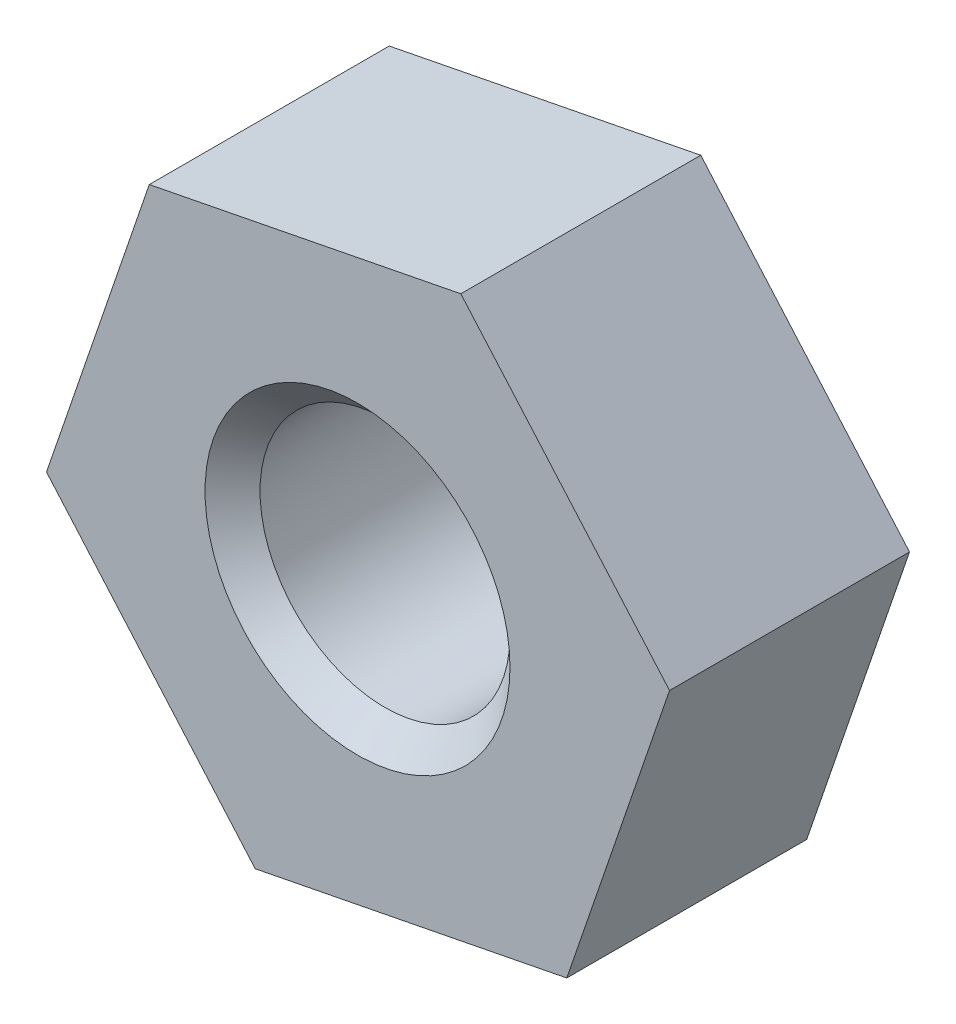
SolidWorks part; units mm, degrees
ref_plane "Front Plane" through (0, 0, 0) normal (0, 0, 1) x (1, 0, 0)
ref_plane "Top Plane" through (0, 0, 0) normal (0, 1, 0) x (1, 0, 0)
ref_plane "Right Plane" through (0, 0, 0) normal (1, 0, 0) x (0, 0, -1)
sketch "Sketch1" plane through (0, 0, 0) normal (0, 0, 1) x (1, 0, 0)
  line L1 (2.0878, -2.3926) -> (3.1159, 0.6118)
  line L2 (3.1159, 0.6118) -> (1.0281, 3.0044)
  line L3 (1.0281, 3.0044) -> (-2.0878, 2.3926)
  line L4 (-2.0878, 2.3926) -> (-3.1159, -0.6118)
  line L5 (-3.1159, -0.6118) -> (-1.0281, -3.0044)
  line L6 (-1.0281, -3.0044) -> (2.0878, -2.3926)
  circle A0 centre (0, 0) radius 2.75 construction
  dimension "D1" = 5.5
extrude "Boss-Extrude1" add sketch "Sketch1" along normal blind 2.4
hole_wizard "M3 Tapped Hole3" positions "3DSketch5" profile "Sketch5" tap size "M3" standard "ISO" end condition through all
sketch3d "3DSketch5"
  point P0 (-0.005, 0.0161, 2.4)
sketch "Sketch5" plane through (-0.005, 0.0161, 2.4) normal (1, 0, 0) x (0, -1, 0)
  line L0 (0, 0) -> (0, 2.4)
  line L1 (0, 2.4) -> (1.25, 2.4)
  line L2 (1.25, 2.4) -> (1.25, 0.275)
  line L3 (1.25, 0.275) -> (1.525, 0)
  line L5 (1.525, 0) -> (0, 0)
  line L6 (-1.25, 0.275) -> (-1.525, 0) construction
  line L11 (0, -6.35) -> (0, 107.95) construction
  dimension "Thru Tap Drill Dia." = 2.5
  dimension "Thru Tap Drill Depth" = 2.4
  dimension "Near C'Sink Dia." = 3.05
  dimension "Near C'Sink Angle" = 90
cosmetic thread "Hole Thread6" parameters "D2"=3
